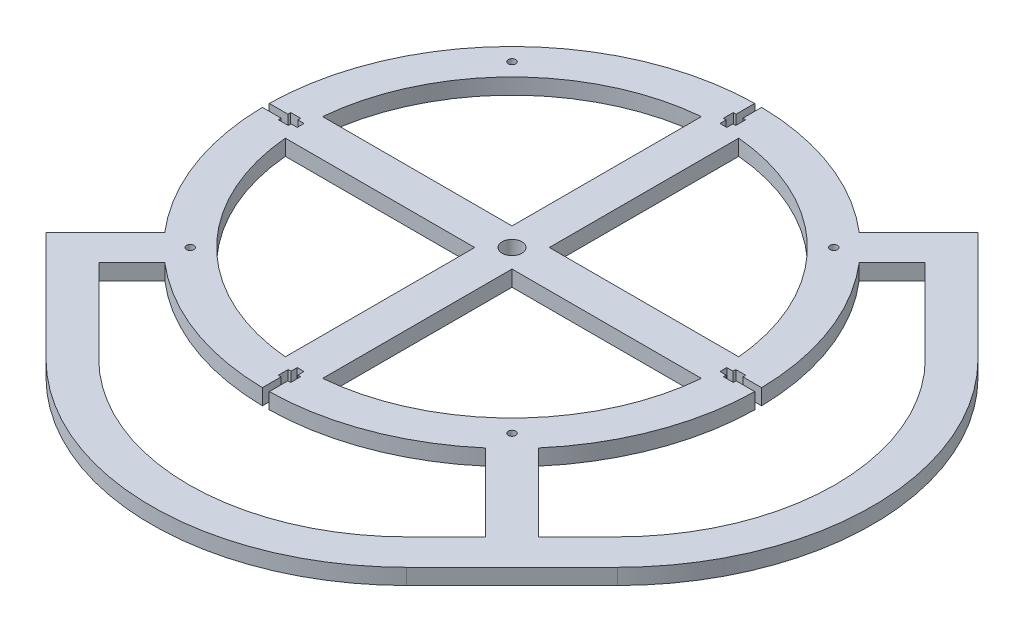
SolidWorks part; units mm, degrees
ref_plane "Front Plane" through (0, 0, 0) normal (0, 0, 1) x (1, 0, 0)
ref_plane "Top Plane" through (0, 0, 0) normal (0, 1, 0) x (1, 0, 0)
ref_plane "Right Plane" through (0, 0, 0) normal (1, 0, 0) x (0, 0, -1)
sketch "Sketch1" plane through (0, 0, 0) normal (0, 1, 0) x (1, 0, 0)
  line L0 (0, -99) -> (0, 99) construction
  line L1 (-99, 0) -> (99, 0) construction
  line L2 (-98.7155, -7.5) -> (98.7155, -7.5)
  line L3 (7.5, -98.7155) -> (7.5, 98.7155)
  line L4 (-98.7155, 7.5) -> (98.7155, 7.5)
  line L5 (-7.5, -98.7155) -> (-7.5, 98.7155)
  line L6 (-7.5, -99) -> (-7.5, 99) construction
  line L7 (7.5, -99) -> (7.5, 99) construction
  line L8 (-99, -7.5) -> (99, -7.5) construction
  line L9 (-99, 7.5) -> (99, 7.5) construction
  line L10 (-88.3883, -88.3883) -> (17.6777, -194.4544) construction
  line L11 (17.6777, -194.4544) -> (194.4544, -17.6777) construction
  line L12 (194.4544, -17.6777) -> (88.3883, 88.3883) construction
  line L13 (0, 0) -> (33755.9757, 33755.9757) construction
  line L14 (-88.3883, -88.3883) -> (-70.0036, -70.0036) construction
  line L15 (88.3883, 88.3883) -> (70.0036, 70.0036) construction
  line L16 (106.066, -106.066) -> (70.0036, -70.0036) construction
  line L17 (111.3693, -100.7627) -> (75.1057, -64.4991)
  line L18 (88.3883, 77.7817) -> (75.1057, 64.4991) construction
  line L19 (183.8478, -17.6777) -> (88.3883, 77.7817) construction
  line L20 (17.6777, -183.8478) -> (183.8478, -17.6777) construction
  line L21 (-77.7817, -88.3883) -> (17.6777, -183.8478) construction
  line L22 (-77.7817, -88.3883) -> (-64.4991, -75.1057) construction
  line L23 (100.7627, -111.3693) -> (64.4991, -75.1057)
  line L24 (88.3883, 98.9949) -> (64.4991, 75.1057)
  line L25 (205.061, -17.6777) -> (88.3883, 98.9949) construction
  line L26 (17.6777, -205.061) -> (205.061, -17.6777) construction
  line L27 (-98.9949, -88.3883) -> (17.6777, -205.061) construction
  line L28 (-98.9949, -88.3883) -> (-75.1057, -64.4991)
  line L29 (-77.7817, -88.3883) -> (-64.7003, -75.3069) construction
  line L30 (-98.9949, -88.3883) -> (-75.3069, -64.7003) construction
  line L31 (88.3883, 77.7817) -> (75.3069, 64.7003) construction
  line L32 (88.3883, 98.9949) -> (64.7003, 75.3069) construction
  line L33 (111.3693, -100.7627) -> (75.3069, -64.7003) construction
  line L34 (100.7627, -111.3693) -> (64.7003, -75.3069) construction
  line L35 (90.1561, -132.5825) -> (132.5825, -90.1561)
  line L36 (-98.9949, -88.3883) -> (-54.8008, -132.5825)
  line L37 (88.3883, 98.9949) -> (132.5825, 54.8008)
  line L38 (-54.8008, -132.5825) -> (132.5825, 54.8008) construction
  line L39 (-77.7817, -88.3883) -> (-64.4991, -75.1057)
  line L40 (-77.7817, -88.3883) -> (-44.1942, -121.9759)
  line L41 (79.5495, -121.9759) -> (121.9759, -79.5495)
  line L42 (88.3883, 77.7817) -> (121.9759, 44.1942)
  line L43 (88.3883, 77.7817) -> (75.1057, 64.4991)
  line L44 (-75.1057, -64.4991) -> (-64.4991, -75.1057)
  line L45 (64.4991, 75.1057) -> (75.1057, 64.4991)
  circle A0 centre (0, 0) radius 100 construction
  circle A1 centre (0, 0) radius 99
  circle A2 centre (0, 0) radius 84
  circle A3 centre (0, 0) radius 157.5 construction
  circle A5 centre (0, 0) radius 132.7121 construction
  arc A6 (90.1561, -132.5825) -> (-54.8008, -132.5825) centre (17.6777, -60.1041) cw
  arc A7 (132.5825, -90.1561) -> (132.5825, 54.8008) centre (60.1041, -17.6777) ccw
  arc A8 (79.5495, -121.9759) -> (-44.1942, -121.9759) centre (17.6777, -60.1041) cw
  arc A9 (121.9759, -79.5495) -> (121.9759, 44.1942) centre (60.1041, -17.6777) ccw
  point P7 (0, 0)
  point P11 (0, 0)
  point P65 (111.3693, -111.3693)
  dimension "D1" = 200
  dimension "D2" = 1
  dimension "D3" = 15
  dimension "D6" = 25
  dimension "D7" = 25
  dimension "D8" = 50
  dimension "D9" = 15
  dimension "D10" = 45
  dimension "D13" = 60
  dimension "D4" = 7.5
  dimension "D5" = 7.5
  dimension "D11" = 7.5
  dimension "D12" = 7.5
  dimension "D14" = 15
extrude "Boss-Extrude1" add sketch "Sketch1" along normal mid plane 6.35
sketch "Sketch2" plane through (0, 0, 0) normal (0, 1, 0) x (1, 0, 0)
  line L0 (-1.375, 85) -> (-1.375, 99)
  line L1 (-1.375, 85) -> (1.375, 85)
  line L2 (-1.375, 99) -> (1.375, 99)
  line L3 (1.375, 85) -> (1.375, 99)
  line L4 (-1.375, 85) -> (1.375, 99) construction
  line L5 (-1.375, 99) -> (1.375, 85) construction
  line L6 (-2.5, 87.5) -> (-2.5, 91.5)
  line L7 (-2.5, 87.5) -> (2.5, 87.5)
  line L8 (-2.5, 91.5) -> (2.5, 91.5)
  line L9 (2.5, 87.5) -> (2.5, 91.5)
  line L10 (-2.5, 87.5) -> (2.5, 91.5) construction
  line L11 (-2.5, 91.5) -> (2.5, 87.5) construction
  line L12 (0, -1000) -> (0, 49000) construction
  line L13 (-1000, 0) -> (49000, 0) construction
  circle A0 centre (0, 0) radius 99 construction
  point P1 (0, 92)
  point P2 (0, 89.5)
  dimension "D1" = 2.75
  dimension "D2" = 14
  dimension "D3" = 4
  dimension "D4" = 5
  dimension "D5" = 2.5
extrude "Cut-Extrude1" cut sketch "Sketch2" against normal through all both and the other way through all contours L7 L0 L1 L3 | L8 L0 L7 L3 | L7 L9 L8 L3 | L0 L8 L3 L2 | L8 L6 L7 L0
pattern_circular "CirPattern1" count 4 over 360 about axis through (0, 0, 0) along (0, 1, 0) of "Cut-Extrude1"
hole_wizard "Ø3.0 (3) Diameter Hole1" positions "Sketch3" profile "Sketch4" hole size "Ø3.0" standard "ANSI Metric" end condition up to next
sketch "Sketch3" plane through (0, 3.175, 0) normal (0, 1, 0) x (1, 0, 0)
  line L0 (-70.0036, -70.0036) -> (70.0036, 70.0036) construction
  line L2 (-70.0036, 70.0036) -> (70.0036, -70.0036) construction
  line L4 (70.0036, 70.0036) -> (59.397, 59.397)
  line L6 (70.0036, -70.0036) -> (59.397, -59.397)
  line L8 (-70.0036, -70.0036) -> (-59.397, -59.397)
  line L10 (-70.0036, 70.0036) -> (-59.397, 59.397)
  arc A2 (83.6645, 7.5) -> (7.5, 83.6645) centre (0, 0) ccw construction
  arc A3 (7.5, -83.6645) -> (83.6645, -7.5) centre (0, 0) ccw construction
  arc A4 (-83.6645, -7.5) -> (-7.5, -83.6645) centre (0, 0) ccw construction
  arc A5 (-7.5, 83.6645) -> (-83.6645, 7.5) centre (0, 0) ccw construction
  circle A6 centre (0, 0) radius 99
  arc A7 (-1.375, 98.9905) -> (-98.9905, 1.375) centre (0, 0) ccw construction
  point P107 (0, 0)
  point P324 (0, 0)
  point P360 (-64.7003, 64.7003)
  point P362 (64.7003, 64.7003)
  point P364 (64.7003, -64.7003)
  point P366 (-64.7003, -64.7003)
sketch "Sketch4" plane through (-64.7003, 3.175, 64.7003) normal (1, 0, 0) x (0, 0, 1)
  line L0 (0, 0) -> (0, 6.35)
  line L1 (0, 6.35) -> (1.5, 6.35)
  line L2 (1.5, 6.35) -> (1.5, 0)
  line L5 (1.5, 0) -> (0, 0)
  line L11 (0, -6.35) -> (0, 107.95) construction
  dimension "Thru Hole Dia." = 3
  dimension "Thru Hole Depth" = 6.35
hole_wizard "Ø8.0 (8) Diameter Hole1" positions "Sketch5" profile "Sketch6" hole size "Ø8.0" standard "ANSI Metric" end condition up to next
sketch "Sketch5" plane through (0, 3.175, 0) normal (0, 1, 0) x (1, 0, 0)
  point P0 (0, 0)
sketch "Sketch6" plane through (0, 3.175, 0) normal (1, 0, 0) x (0, 0, 1)
  line L0 (0, 0) -> (0, 6.35)
  line L1 (0, 6.35) -> (4, 6.35)
  line L2 (4, 6.35) -> (4, 0)
  line L5 (4, 0) -> (0, 0)
  line L11 (0, -6.35) -> (0, 107.95) construction
  dimension "Thru Hole Dia." = 8
  dimension "Thru Hole Depth" = 6.35
